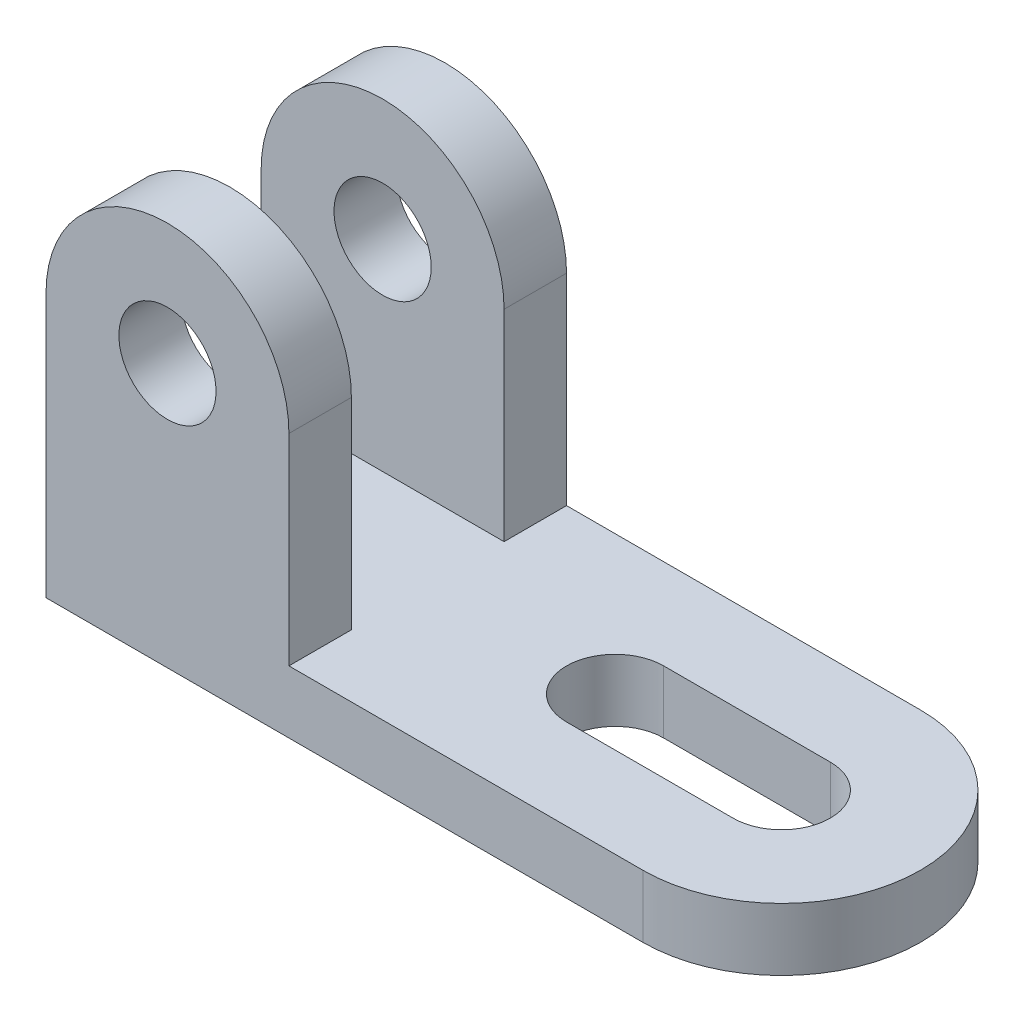
SolidWorks part; units mm, degrees
ref_plane "Front Plane" through (0, 0, 0) normal (0, 0, 1) x (1, 0, 0)
ref_plane "Top Plane" through (0, 0, 0) normal (0, 1, 0) x (1, 0, 0)
ref_plane "Right Plane" through (0, 0, 0) normal (1, 0, 0) x (0, 0, -1)
sketch "Sketch2" plane through (0, 0, 0) normal (0, 1, 0) x (1, 0, 0)
  line L0 (-24, 7) -> (0, 7)
  line L1 (0, -55) -> (0, 55) construction
  line L2 (-24, -7) -> (0, -7)
  line L3 (0, -20) -> (-86, -20)
  line L4 (0, 20) -> (-86, 20)
  line L5 (-86, 20) -> (-86, -20)
  arc A0 (0, 7) -> (0, -7) centre (0, 0) cw
  arc A1 (-24, 7) -> (-24, -7) centre (-24, 0) ccw
  arc A3 (0, -20) -> (0, 20) centre (0, 0) ccw
  dimension "D3" = 20
  dimension "D1" = 14
  dimension "D2" = 24
  dimension "D4" = 86
extrude "Boss-Extrude1" add sketch "Sketch2" along normal blind 9
sketch "Sketch4" plane through (0, 0, 20) normal (0, 0, 1) x (1, 0, 0)
  line L0 (-86, 0) -> (-86, 38)
  line L1 (-51, 38) -> (-51, 0)
  line L2 (-86, 0) -> (0, 0) construction
  line L3 (-51, 0) -> (-86, 0)
  arc A0 (-86, 38) -> (-51, 38) centre (-68.5, 38) cw
  circle A1 centre (-68.5, 38) radius 7
  dimension "D2" = 14
  dimension "D3" = 17.5
  dimension "D1" = 38
extrude "Boss-Extrude2" add sketch "Sketch4" against normal blind 9
mirror "Mirror1" about plane through (0, 0, 0) normal (0, 0, 1) of "Boss-Extrude2"
